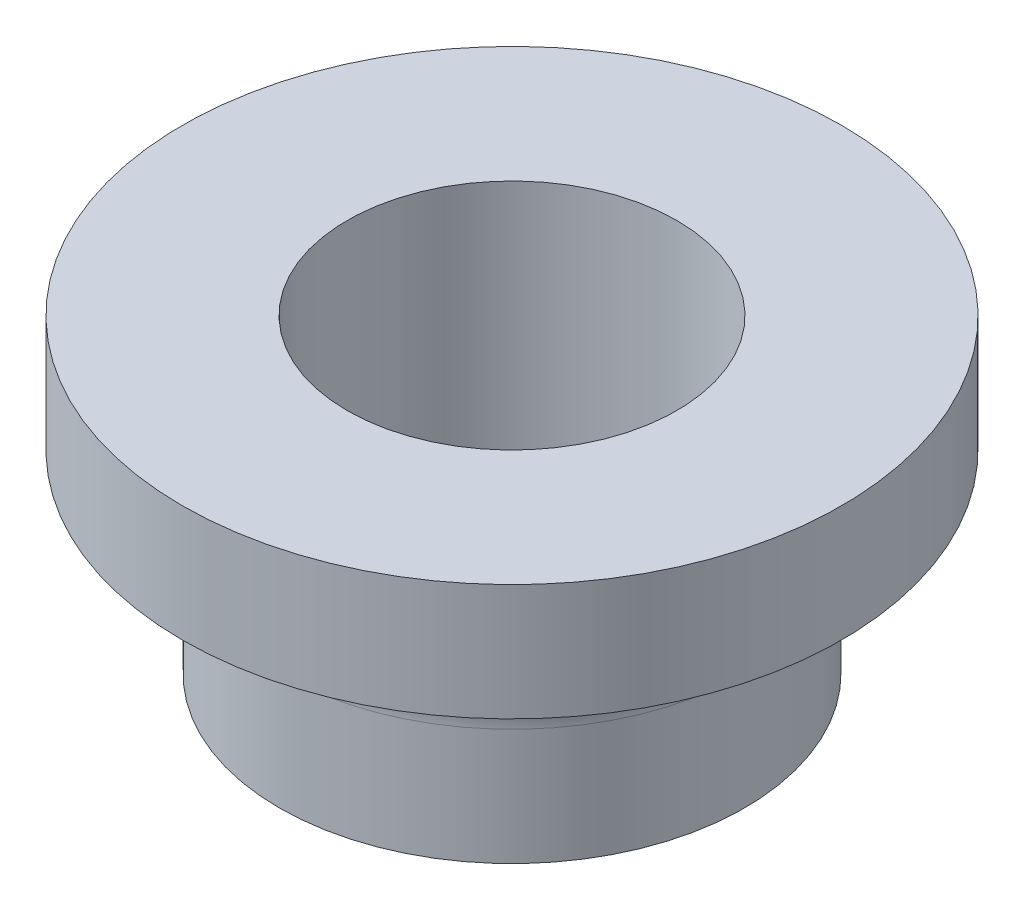
SolidWorks part; units mm, degrees
ref_plane "Front Plane" through (0, 0, 0) normal (0, 0, 1) x (1, 0, 0)
ref_plane "Top Plane" through (0, 0, 0) normal (0, 1, 0) x (1, 0, 0)
ref_plane "Right Plane" through (0, 0, 0) normal (1, 0, 0) x (0, 0, -1)
sketch "Sketch1" plane through (0, 0, 0) normal (0, 1, 0) x (1, 0, 0)
  circle A0 centre (0, 0) radius 6
  dimension "D1" = 12
extrude "Boss-Extrude1" add sketch "Sketch1" along normal blind 5
sketch "Sketch2" plane through (0, 5, 0) normal (0, 1, 0) x (1, 0, 0)
  circle A0 centre (0, 0) radius 8.5
  dimension "D1" = 17
extrude "Boss-Extrude2" add sketch "Sketch2" along normal blind 3
fillet "Fillet1" radius 2 1 edges at (0, 5, 6)
sketch "Sketch3" plane through (0, 8, 0) normal (0, 1, 0) x (1, 0, 0)
  circle A0 centre (0, 0) radius 4.25
  dimension "D1" = 8.5
extrude "Cut-Extrude1" cut sketch "Sketch3" against normal blind 8
